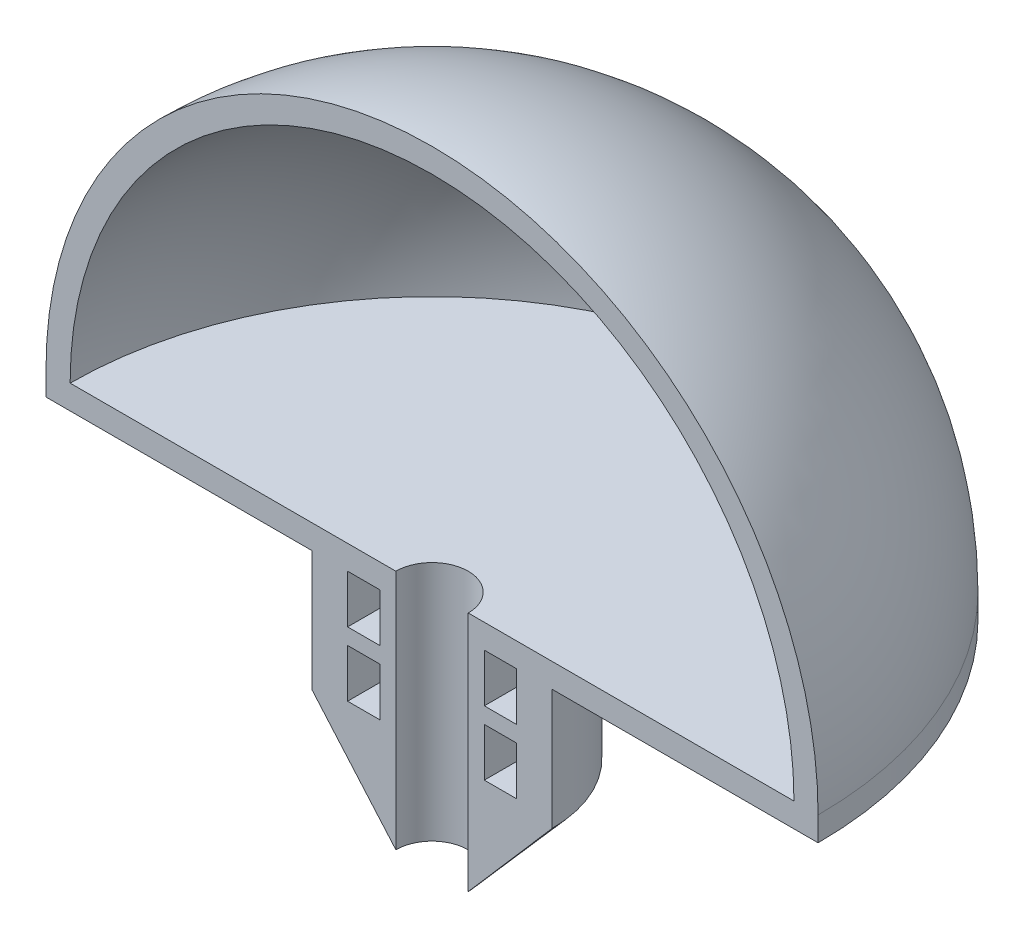
SolidWorks part; units mm, degrees
ref_plane "Alzado" through (0, 0, 0) normal (0, 0, 1) x (1, 0, 0)
ref_plane "Planta" through (0, 0, 0) normal (0, 1, 0) x (1, 0, 0)
ref_plane "Vista lateral" through (0, 0, 0) normal (1, 0, 0) x (0, 0, -1)
sketch "Croquis1" plane through (0, 0, 0) normal (0, 0, 1) x (1, 0, 0)
  line L0 (-51.7822, -4.3826) -> (-31.5322, -4.3826)
  line L1 (-29.2822, 19.6174) -> (-29.2822, 18.1174)
  line L2 (-53.2822, -5.8826) -> (-43.2485, -5.8826)
  line L3 (-31.5322, -4.3826) -> (-31.5322, -14.3826)
  line L4 (-53.2822, -4.3826) -> (-53.2822, -5.8826)
  line L5 (-36.7485, -13.3721) -> (-31.5322, -19.3826)
  line L6 (-43.2485, -5.8826) -> (-36.7485, -5.8826)
  line L7 (-31.5322, -19.3826) -> (-31.5322, -14.3826)
  line L8 (-36.7485, -5.8826) -> (-36.7485, -13.3721)
  arc A0 (-29.2822, 18.1174) -> (-51.7822, -4.3826) centre (-29.2822, -4.3826) ccw
  arc A1 (-53.2822, -4.3826) -> (-29.2822, 19.6174) centre (-29.2822, -4.3826) cw
  dimension "D1" = 1.5
  dimension "D2" = 1.5
revolve "Revolución1" add sketch "Croquis1" angle 180 about L1
sketch "Croquis2" plane through (0, 0, 0) normal (0, 0, 1) x (1, 0, 0)
  line L1 (-34.5322, -5.8826) -> (-32.5322, -5.8826)
  line L2 (-34.5322, -5.8826) -> (-34.5322, -8.8826)
  line L3 (-34.5322, -8.8826) -> (-32.5322, -8.8826)
  line L4 (-32.5322, -5.8826) -> (-32.5322, -8.8826)
  line L5 (-31.5322, -19.3826) -> (-31.5322, -4.3826) construction
  line L11 (-26.0322, -5.8826) -> (-24.0322, -5.8826)
  line L12 (-26.0322, -5.8826) -> (-26.0322, -8.8826)
  line L13 (-26.0322, -8.8826) -> (-24.0322, -8.8826)
  line L14 (-24.0322, -5.8826) -> (-24.0322, -8.8826)
  line L15 (-26.0322, -9.8826) -> (-24.0322, -9.8826)
  line L16 (-26.0322, -9.8826) -> (-26.0322, -12.8826)
  line L17 (-26.0322, -12.8826) -> (-24.0322, -12.8826)
  line L18 (-24.0322, -9.8826) -> (-24.0322, -12.8826)
  line L19 (-34.5322, -9.8826) -> (-32.5322, -9.8826)
  line L20 (-34.5322, -9.8826) -> (-34.5322, -12.8826)
  line L21 (-34.5322, -12.8826) -> (-32.5322, -12.8826)
  line L22 (-32.5322, -9.8826) -> (-32.5322, -12.8826)
  dimension "D1" = 2
  dimension "D4" = 1
  dimension "D5" = 2
  dimension "D6" = 2
extrude "Cortar-Extruir1" cut sketch "Croquis2" against normal blind 15
sketch "Croquis3" plane through (-26.0322, 0, 0) normal (1, 0, 0) x (0, 0, -1)
  line L0 (6.7219, -12.8826) -> (0, -12.8826) construction
  line L1 (4.7831, -12.8826) -> (11.8594, -12.8826)
  line L2 (4.7831, -12.8826) -> (4.7831, -9.8826)
  line L3 (4.7831, -9.8826) -> (11.8594, -9.8826)
  line L4 (11.8594, -12.8826) -> (11.8594, -9.8826)
  line L5 (6.7219, -8.8826) -> (0, -8.8826) construction
  line L6 (4.7831, -8.8826) -> (11.472, -8.8826)
  line L7 (4.7831, -8.8826) -> (4.7831, -5.8826)
  line L8 (4.7831, -5.8826) -> (11.472, -5.8826)
  line L9 (11.472, -8.8826) -> (11.472, -5.8826)
extrude "Cortar-Extruir2" cut sketch "Croquis3" against normal up to vertex (6.5 mm away) up to point (-32.5322, -8.8826, -6.7219)
